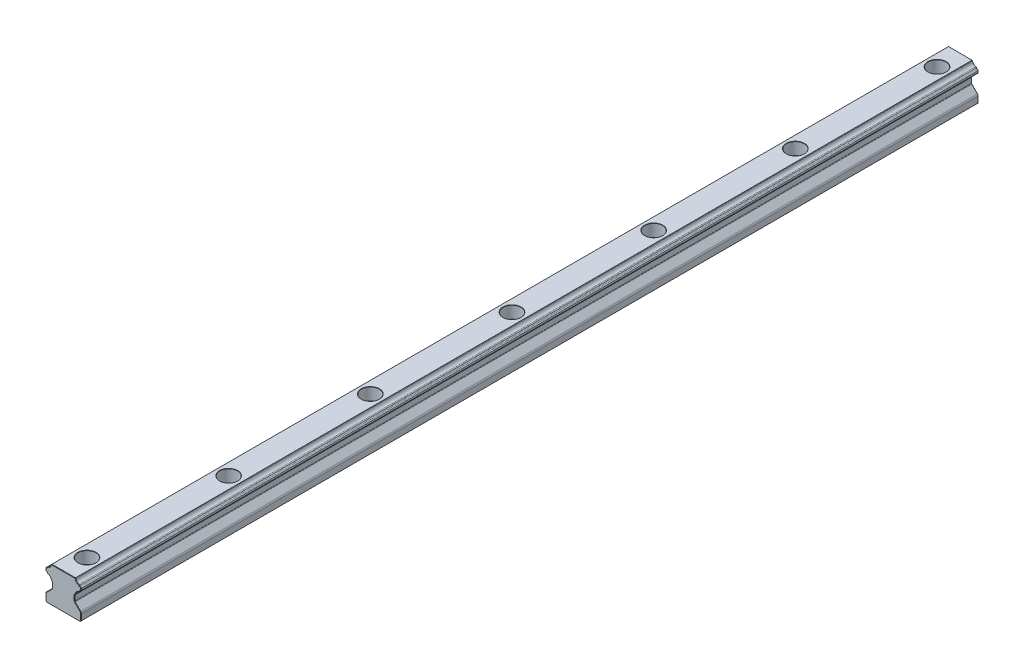
SolidWorks part; units mm, degrees
material "Plain Carbon Steel"
ref_plane "Front Plane" through (0, 0, 0) normal (0, 0, 1) x (1, 0, 0)
ref_plane "Top Plane" through (0, 0, 0) normal (0, 1, 0) x (1, 0, 0)
ref_plane "Right Plane" through (0, 0, 0) normal (1, 0, 0) x (0, 0, -1)
sketch "Rail Profile" plane through (0, 0, 0) normal (0, 0, 1) x (1, 0, 0)
  line L47 (0, 0) -> (0, 20) construction
  line L48 (-7, 0) -> (7, 0)
  line L49 (7, 0) -> (7.5, 0.5)
  line L50 (7.5, 0.5) -> (7.5, 3.0858)
  line L58 (7.2071, 3.7929) -> (4.8672, 6.1328)
  line L59 (4.75, 6.4157) -> (4.75, 8.5843)
  line L60 (4.8672, 8.8672) -> (5.063, 9.063)
  line L61 (7.5, 11.6657) -> (7.5, 12.3343)
  line L62 (-7, 0) -> (-7.5, 0.5)
  line L63 (5, 15) -> (-5, 15)
  line L64 (6.75, 9) -> (6.75, 15) construction
  line L65 (5.063, 14.937) -> (5, 15)
  line L66 (-7.5, 0.5) -> (-7.5, 3.0858)
  line L67 (6.75, 15) -> (3.75, 12) construction
  line L68 (3.75, 12) -> (6.75, 9) construction
  line L69 (7.1, 12.3343) -> (7.1, 11.6657) construction
  line L70 (6.4042, 13.0301) -> (6.4042, 10.9699) construction
  line L71 (-7.2071, 3.7929) -> (-4.8672, 6.1328)
  line L72 (-4.75, 6.4157) -> (-4.75, 8.5843)
  line L73 (-4.8672, 8.8672) -> (-5.063, 9.063)
  line L74 (5, 15) -> (8, 12) construction
  line L75 (4.8672, 8.8672) -> (8, 12) construction
  line L76 (-7.5, 11.6657) -> (-7.5, 12.3343)
  line L77 (-5.063, 14.937) -> (-5, 15)
  arc A4 (6.4734, 13.4241) -> (5.1741, 14.7234) centre (6.75, 15) cw
  arc A6 (5.1741, 9.2766) -> (6.4734, 10.5759) centre (6.75, 9) cw
  arc A7 (7.2071, 3.7929) -> (7.5, 3.0858) centre (6.5, 3.0858) cw
  arc A8 (5.063, 14.937) -> (5.1741, 14.7234) centre (4.7801, 14.6542) cw
  arc A9 (6.4734, 13.4241) -> (6.8012, 13.0792) centre (6.4042, 13.0301) cw
  arc A10 (7.1491, 12.7313) -> (7.5, 12.3343) centre (7.1, 12.3343) cw
  arc A11 (7.5, 11.6657) -> (7.1491, 11.2687) centre (7.1, 11.6657) cw
  arc A12 (6.8012, 10.9208) -> (6.4734, 10.5759) centre (6.4042, 10.9699) cw
  arc A13 (5.1741, 9.2766) -> (5.063, 9.063) centre (4.7801, 9.3458) cw
  arc A14 (4.8672, 8.8672) -> (4.75, 8.5843) centre (5.15, 8.5843) ccw
  arc A15 (4.75, 6.4157) -> (4.8672, 6.1328) centre (5.15, 6.4157) ccw
  arc A16 (6.8012, 13.0792) -> (7.1491, 12.7313) centre (7.1981, 13.1283) ccw
  arc A17 (7.1491, 11.2687) -> (6.8012, 10.9208) centre (7.1981, 10.8717) ccw
  arc A18 (-7.2071, 3.7929) -> (-7.5, 3.0858) centre (-6.5, 3.0858) ccw
  arc A19 (-4.75, 6.4157) -> (-4.8672, 6.1328) centre (-5.15, 6.4157) cw
  arc A20 (-4.8672, 8.8672) -> (-4.75, 8.5843) centre (-5.15, 8.5843) cw
  arc A21 (-5.1741, 9.2766) -> (-5.063, 9.063) centre (-4.7801, 9.3458) ccw
  arc A22 (-5.1741, 9.2766) -> (-6.4734, 10.5759) centre (-6.75, 9) ccw
  arc A23 (-6.8012, 10.9208) -> (-6.4734, 10.5759) centre (-6.4042, 10.9699) ccw
  arc A24 (-7.1491, 11.2687) -> (-6.8012, 10.9208) centre (-7.1981, 10.8717) cw
  arc A25 (-7.5, 11.6657) -> (-7.1491, 11.2687) centre (-7.1, 11.6657) ccw
  arc A26 (-7.1491, 12.7313) -> (-7.5, 12.3343) centre (-7.1, 12.3343) ccw
  arc A27 (-6.8012, 13.0792) -> (-7.1491, 12.7313) centre (-7.1981, 13.1283) cw
  arc A28 (-6.4734, 13.4241) -> (-6.8012, 13.0792) centre (-6.4042, 13.0301) ccw
  arc A29 (-6.4734, 13.4241) -> (-5.1741, 14.7234) centre (-6.75, 15) ccw
  arc A30 (-5.063, 14.937) -> (-5.1741, 14.7234) centre (-4.7801, 14.6542) ccw
  point P2 (4.75, 7.5)
  point P12 (7.5, 12)
  point P19 (6.75, 12)
  point P25 (5.1578, 14.8422)
  point P50 (8, 12)
  point P78 (0, 15)
  dimension "Rb" = 1.6
  dimension "Rf1" = 1
  dimension "Rf2" = 0.4
  dimension "WR" = 15
  dimension "Wi" = 9.5
  dimension "Wt" = 5
  dimension "Ac" = 135
  dimension "HR" = 15
  dimension "Hm" = 7.5
  dimension "Hb" = 12
  dimension "Hc" = 0.5
  dimension "Wb" = 7.5
extrude "Body" add sketch "Rail Profile" against normal blind 380
chamfer "Aesthetic Chamfer" distance 0.15 angle 45 84 edges at (-5.0315, 14.9685, 0) (-5.135, 14.8388, 0) (-5.6186, 13.8686, 0) (-6.6941, 13.3057, 0) (-6.9153, 12.8454, 0) (-7.3997, 12.5992, 0) (-7.5, 12, 0) (-7.3997, 11.4008, 0) (-6.9153, 11.1546, 0) (-6.6941, 10.6943, 0) (-5.6186, 10.1314, 0) (-5.135, 9.1612, 0) (-4.9651, 8.9651, 0) (-4.7804, 8.7374, 0) (-4.75, 7.5, 0) (-4.7804, 6.2626, 0) (-6.0371, 4.9629, 0) (-7.4239, 3.4685, 0) (-7.5, 1.7929, 0) (-7.25, 0.25, 0) (0, 0, 0) (7.25, 0.25, 0) (5.0315, 14.9685, 0) (5.135, 14.8388, 0) (5.6186, 13.8686, 0) (6.6941, 13.3057, 0) (6.9153, 12.8454, 0) (7.3997, 12.5992, 0) (7.5, 12, 0) (7.3997, 11.4008, 0) (6.9153, 11.1546, 0) (6.6941, 10.6943, 0) (5.6186, 10.1314, 0) (5.135, 9.1612, 0) (4.9651, 8.9651, 0) (4.7804, 8.7374, 0) (7.5, 1.7929, 0) (4.75, 7.5, 0) (7.4239, 3.4685, 0) (4.7804, 6.2626, 0) (6.0371, 4.9629, 0) (0, 15, 0) (5.0315, 14.9685, -380) (5.135, 14.8388, -380) (5.6186, 13.8686, -380) (6.6941, 13.3057, -380) (6.9153, 12.8454, -380) (7.3997, 12.5992, -380) (7.5, 12, -380) (7.3997, 11.4008, -380) (6.9153, 11.1546, -380) (6.6941, 10.6943, -380) (5.6186, 10.1314, -380) (5.135, 9.1612, -380) (4.9651, 8.9651, -380) (4.7804, 8.7374, -380) (4.75, 7.5, -380) (4.7804, 6.2626, -380) (6.0371, 4.9629, -380) (7.4239, 3.4685, -380) (7.5, 1.7929, -380) (7.25, 0.25, -380) (0, 0, -380) (-7.25, 0.25, -380) (-5.0315, 14.9685, -380) (-5.135, 14.8388, -380) (-5.6186, 13.8686, -380) (-6.6941, 13.3057, -380) (-6.9153, 12.8454, -380) (-7.3997, 12.5992, -380) (-7.5, 12, -380) (-7.3997, 11.4008, -380) (-6.9153, 11.1546, -380) (-6.6941, 10.6943, -380) (-5.6186, 10.1314, -380) (-7.5, 1.7929, -380) (-5.135, 9.1612, -380) (-7.4239, 3.4685, -380) (-4.9651, 8.9651, -380) (-6.0371, 4.9629, -380) (-4.7804, 8.7374, -380) (-4.7804, 6.2626, -380) (-4.75, 7.5, -380) (0, 15, -380)
hole_wizard "Mounting Hole" positions "3DSketch1" profile "Sketch1" counterbore size "M4" standard "ISO" end condition through all
sketch3d "3DSketch1"
  line L1 (0, 15, -379.85) -> (0, 15, -0.15) construction
  line L2 (5, 15, -379.85) -> (-5, 15, -379.85) construction
  line L3 (-5, 15, -0.15) -> (5, 15, -0.15) construction
  point P0 (0, 15, -190)
  dimension "D1" = 7.5
  dimension "E1" = 190
sketch "Sketch1" plane through (0, 15, -190) normal (1, 0, 0) x (0, 0, 1)
  line L0 (0, 0) -> (0, 15)
  line L1 (2.25, 14.9) -> (2.35, 15)
  line L2 (2.25, 14.9) -> (2.25, 5.4)
  line L3 (2.25, 5.4) -> (2.35, 5.3)
  line L4 (2.35, 5.3) -> (3.75, 5.3)
  line L5 (3.75, 5.3) -> (3.75, 0.1)
  line L6 (3.75, 0.1) -> (3.85, 0)
  line L7 (3.85, 0) -> (0, 0)
  line L8 (-3.75, 0.1) -> (-3.85, 0) construction
  line L9 (-2.25, 5.4) -> (-2.35, 5.3) construction
  line L11 (0, -6.35) -> (0, 107.95) construction
  line L12 (2.35, 15) -> (0, 15)
  line L13 (-2.25, 14.9) -> (-2.35, 15) construction
  dimension "Thru Hole Dia." = 4.5
  dimension "Thru Hole Depth" = 15
  dimension "C'Bore Dia." = 7.5
  dimension "C'Bore Depth" = 5.3
  dimension "Near C'Sink Dia." = 7.7
  dimension "Near C'Sink Angle" = 90
  dimension "Mid C'Sink Dia." = 4.7
  dimension "Mid C'Sink Angle" = 90
  dimension "Far C'Sink Dia." = 4.7
  dimension "Far C'Sink Angle" = 90
fillet "Production Fillet" radius 0.1 1 edges at (0, 9.7, -186.25)
pattern_linear "Mounting Holes Pattern" count 4 spacing 60 along (0, 0, -1) count 4 spacing 60 along (0, 0, 1) of "Mounting Hole", "Production Fillet"
equation "\"Wt@Rail Profile\"= \"WR@Rail Profile\" / 3'Top Side Half Width"
equation "\"Hm@Rail Profile\"= \"HR@Rail Profile\" / 2'Recirculation Avoidance Height"
equation "\"Hb@Rail Profile\"= 0.8 * \"HR@Rail Profile\"'Pivot Height"
equation "\"Hc@Rail Profile\"= \"WR@Rail Profile\" / 30'Chamfer Width"
equation "\"Wb@Rail Profile\"= \"WR@Rail Profile\" / 2'Ball Center Cross Width"
equation "\"D1@3DSketch1\"= \"WR@Rail Profile\" / 2'Hole Center Position"
